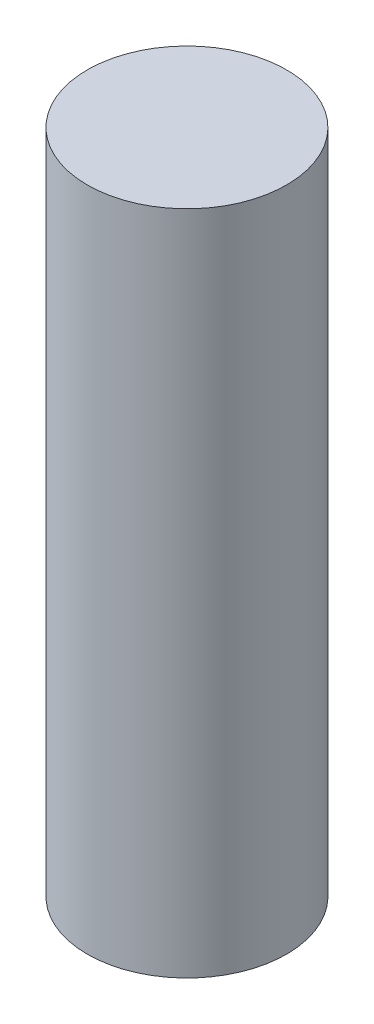
SolidWorks part; units mm, degrees
ref_plane "Front Plane" through (0, 0, 0) normal (0, 0, 1) x (1, 0, 0)
ref_plane "Top Plane" through (0, 0, 0) normal (0, 1, 0) x (1, 0, 0)
ref_plane "Right Plane" through (0, 0, 0) normal (1, 0, 0) x (0, 0, -1)
sketch "Sketch1" plane through (0, 0, 0) normal (0, 1, 0) x (1, 0, 0)
  circle A0 centre (0, 0) radius 10.585
  dimension "D1" = 21.17
extrude "Boss-Extrude1" add sketch "Sketch1" along normal blind 70.73
